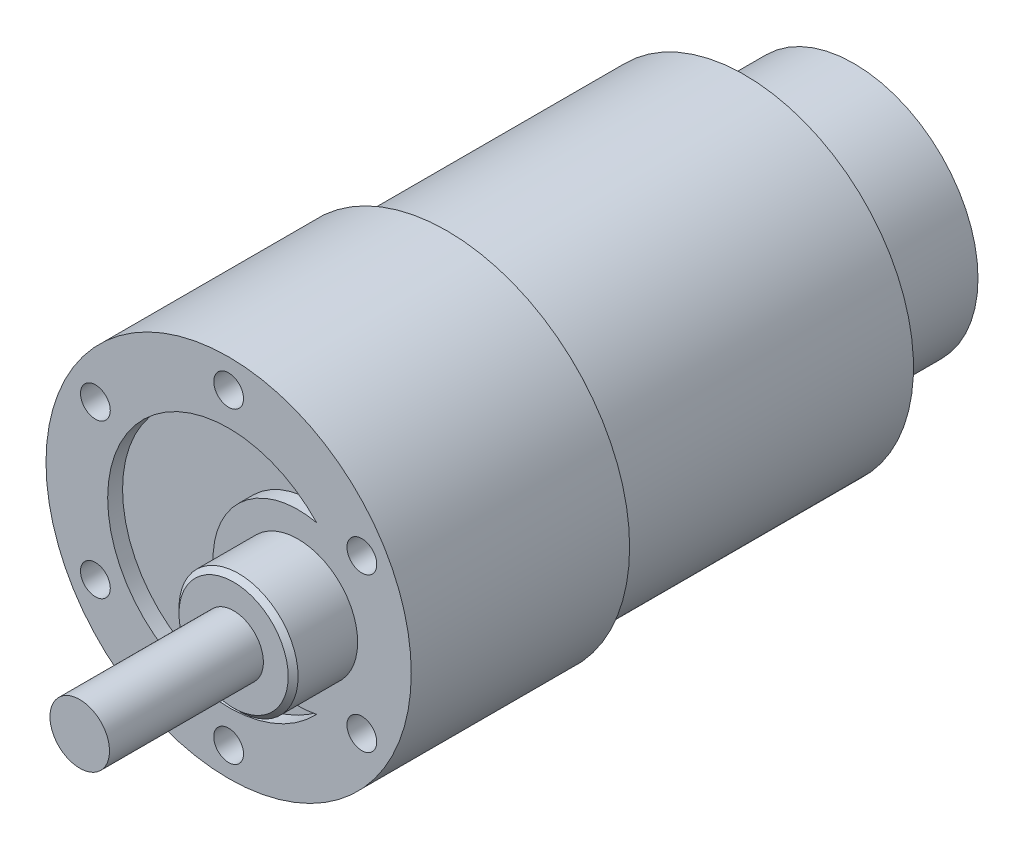
SolidWorks part; units mm, degrees
ref_plane "Front Plane" through (0, 0, 0) normal (0, 0, 1) x (1, 0, 0)
ref_plane "Top Plane" through (0, 0, 0) normal (0, 1, 0) x (1, 0, 0)
ref_plane "Right Plane" through (0, 0, 0) normal (1, 0, 0) x (0, 0, -1)
ref_plane "Plane1" through (0, 0, 0) normal (0, -1, 0) x (1, 0, 0)
sketch "Sketch1" plane through (0, 0, 0) normal (0, -1, 0) x (1, 0, 0)
  line L0 (18.4, 52) -> (0, 52)
  line L1 (0, 52) -> (0, 29)
  line L2 (0, 29) -> (17, 29)
  line L3 (16, 30) -> (18.4, 30)
  line L4 (18.4, 30) -> (18.4, 52)
  line L5 (0, 52) -> (0, 29) construction
  arc A0 (17, 29) -> (16, 30) centre (16, 29) ccw
revolve "Revolve1" add sketch "Sketch1" angle 360 about L5
sketch "Sketch2" plane through (0, 0, 29) normal (0, 0, -1) x (-1, 0, 0)
  circle A0 centre (0, 0) radius 17
extrude "Boss-Extrude1" add sketch "Sketch2" along normal blind 29
sketch "Sketch3" plane through (0, 0, 0) normal (0, 0, -1) x (-1, 0, 0)
  circle A0 centre (0, 0) radius 12.5
extrude "Boss-Extrude2" add sketch "Sketch3" along normal blind 11
sketch "Sketch4" plane through (0, 0, 52) normal (0, 0, 1) x (1, 0, 0)
  arc A0 (8.8681, 8.3597) -> (8.8681, -8.3597) centre (0, 0) ccw
  arc A1 (8.8681, -8.3597) -> (8.8681, 8.3597) centre (7, 0) cw
extrude "Cut-Extrude1" cut sketch "Sketch4" against normal blind 1.5
sketch "Sketch5" plane through (0, 0, 0) normal (0, -1, 0) x (1, 0, 0)
  line L0 (10, 74) -> (7, 74)
  line L1 (7, 74) -> (7, 52)
  line L2 (7, 52) -> (13, 52)
  line L3 (13, 52) -> (13, 58.5)
  line L4 (13, 58.5) -> (10, 58.5)
  line L5 (10, 58.5) -> (10, 74)
  line L6 (7, 74) -> (7, 52) construction
revolve "Revolve2" add sketch "Sketch5" angle 360 about L6
hole_wizard "Ø3.0 (3) Diameter Hole1" positions "Sketch7" profile "Sketch6" hole size "Ø3.0" standard "Ansi Metric"
sketch "Sketch7" plane through (0, 0, 52) normal (0, 0, 1) x (1, 0, 0)
  circle A0 centre (0, 0) radius 15.5 construction
  point P0 (-13.4234, 7.75)
  point P1 (-13.4234, -7.75)
  point P2 (0, -15.5)
  point P3 (13.4234, -7.75)
  point P4 (13.4234, 7.75)
  point P5 (0, 15.5)
  point P13 (7, 0)
  dimension "D1" = 159.653
sketch "Sketch6" plane through (-13.4234, 7.75, 52) normal (1, 0, 0) x (0, -1, 0)
  line L0 (0, 0) -> (0, 3)
  line L1 (0, 3) -> (1.5, 3)
  line L2 (1.5, 3) -> (1.5, 0)
  line L5 (1.5, 0) -> (0, 0)
  line L10 (0, 3) -> (-1.5, 3) construction
  line L11 (0, -6.35) -> (0, 107.95) construction
  dimension "Hole Dia." = 3
  dimension "Hole Depth" = 3
  dimension "Drill Angle" = 180
chamfer "Chamfer1" distance 0.5 angle 45 1 edges at (1, 0, 58.5)
